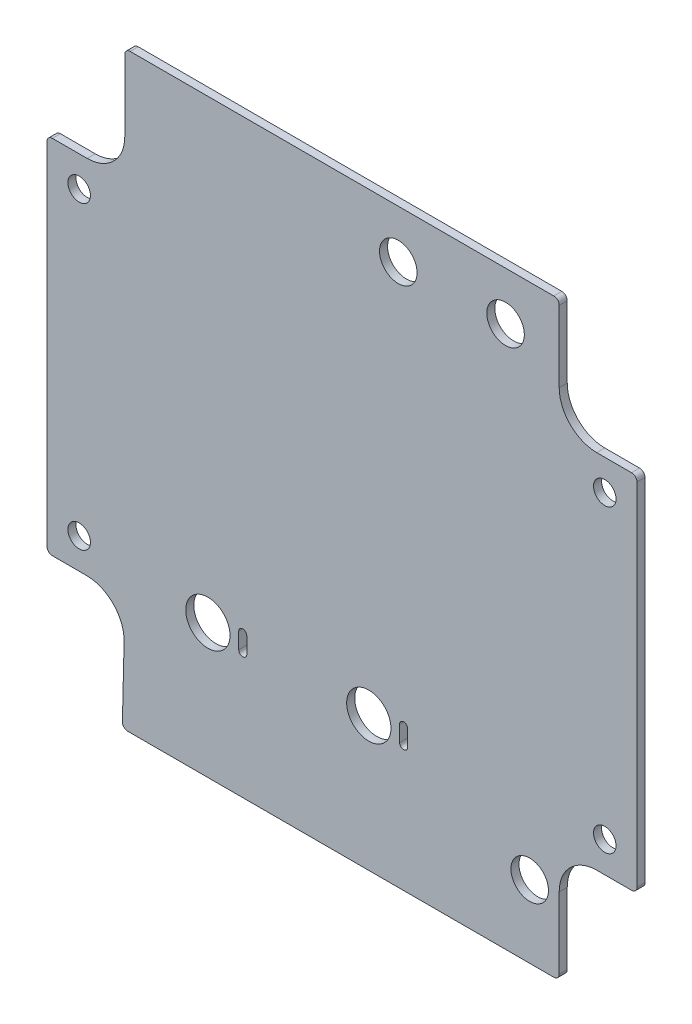
SolidWorks part; units mm, degrees
ref_plane "前基準面" through (0, 0, 0) normal (0, 0, 1) x (1, 0, 0)
ref_plane "上基準面" through (0, 0, 0) normal (0, 1, 0) x (1, 0, 0)
ref_plane "右基準面" through (0, 0, 0) normal (1, 0, 0) x (0, 0, -1)
sketch "草圖1" plane through (0, 0, 0) normal (0, 0, 1) x (1, 0, 0)
  line L27 (9.5192, -18.9462) -> (9.5192, -5.6591)
  line L28 (8.5192, -4.6591) -> (-70.4808, -4.6591)
  line L29 (-71.4808, -5.6591) -> (-71.4808, -18.9462)
  line L30 (-78.4808, -25.9462) -> (-84.9808, -25.9462)
  line L31 (-85.9808, -26.9462) -> (-85.9808, -92.3419)
  line L32 (-84.9834, -93.3419) -> (-78.5836, -93.3586)
  line L33 (-71.6039, -100.5265) -> (-71.9185, -113.6351)
  line L34 (-70.9188, -114.6591) -> (8.5192, -114.6591)
  line L35 (9.5192, -113.6591) -> (9.5192, -100.372)
  line L36 (16.5192, -93.372) -> (23.0192, -93.372)
  line L37 (24.0192, -92.372) -> (24.0192, -26.9462)
  line L38 (23.0192, -25.9462) -> (16.5192, -25.9462)
  line L39 (9.5192, -18.9462) -> (9.5192, -5.6591)
  line L40 (8.5192, -4.6591) -> (-70.4808, -4.6591)
  line L41 (-71.4808, -5.6591) -> (-71.4808, -18.9462)
  line L42 (-78.4808, -25.9462) -> (-84.9808, -25.9462)
  line L43 (-85.9808, -26.9462) -> (-85.9808, -92.3419)
  line L44 (-84.9834, -93.3419) -> (-78.5836, -93.3586)
  line L45 (-71.6039, -100.5265) -> (-71.9185, -113.6351)
  line L46 (-70.9188, -114.6591) -> (8.5192, -114.6591)
  line L47 (9.5192, -113.6591) -> (9.5192, -100.372)
  line L48 (16.5192, -93.372) -> (23.0192, -93.372)
  line L49 (24.0192, -92.372) -> (24.0192, -26.9462)
  line L50 (23.0192, -25.9462) -> (16.5192, -25.9462)
  arc A24 (9.5192, -18.9462) -> (16.5192, -25.9462) centre (16.5192, -18.9462) ccw
  arc A25 (9.5192, -5.6591) -> (8.5192, -4.6591) centre (8.5192, -5.6591) ccw
  arc A26 (-70.4808, -4.6591) -> (-71.4808, -5.6591) centre (-70.4808, -5.6591) ccw
  arc A27 (-78.4808, -25.9462) -> (-71.4808, -18.9462) centre (-78.4808, -18.9462) ccw
  arc A28 (-84.9808, -25.9462) -> (-85.9808, -26.9462) centre (-84.9808, -26.9462) ccw
  arc A29 (-85.9808, -92.3419) -> (-84.9834, -93.3419) centre (-84.9808, -92.3419) ccw
  arc A30 (-71.6039, -100.5265) -> (-78.5836, -93.3586) centre (-78.6019, -100.3586) ccw
  arc A31 (-71.9185, -113.6351) -> (-70.9188, -114.6591) centre (-70.9188, -113.6591) ccw
  arc A32 (8.5192, -114.6591) -> (9.5192, -113.6591) centre (8.5192, -113.6591) ccw
  arc A33 (16.5192, -93.372) -> (9.5192, -100.372) centre (16.5192, -100.372) ccw
  arc A34 (23.0192, -93.372) -> (24.0192, -92.372) centre (23.0192, -92.372) ccw
  arc A35 (24.0192, -26.9462) -> (23.0192, -25.9462) centre (23.0192, -26.9462) ccw
  arc A36 (9.5192, -18.9462) -> (16.5192, -25.9462) centre (16.5192, -18.9462) ccw
  arc A37 (9.5192, -5.6591) -> (8.5192, -4.6591) centre (8.5192, -5.6591) ccw
  arc A38 (-70.4808, -4.6591) -> (-71.4808, -5.6591) centre (-70.4808, -5.6591) ccw
  arc A39 (-78.4808, -25.9462) -> (-71.4808, -18.9462) centre (-78.4808, -18.9462) ccw
  arc A40 (-84.9808, -25.9462) -> (-85.9808, -26.9462) centre (-84.9808, -26.9462) ccw
  arc A41 (-85.9808, -92.3419) -> (-84.9834, -93.3419) centre (-84.9808, -92.3419) ccw
  arc A42 (-71.6039, -100.5265) -> (-78.5836, -93.3586) centre (-78.6019, -100.3586) ccw
  arc A43 (-71.9185, -113.6351) -> (-70.9188, -114.6591) centre (-70.9188, -113.6591) ccw
  arc A44 (8.5192, -114.6591) -> (9.5192, -113.6591) centre (8.5192, -113.6591) ccw
  arc A45 (16.5192, -93.372) -> (9.5192, -100.372) centre (16.5192, -100.372) ccw
  arc A46 (23.0192, -93.372) -> (24.0192, -92.372) centre (23.0192, -92.372) ccw
  arc A47 (24.0192, -26.9462) -> (23.0192, -25.9462) centre (23.0192, -26.9462) ccw
  dimension "D2" = 2
extrude "填料-伸長1" add sketch "草圖1" along normal blind 1.5
hole_wizard "M4 螺旋的螺孔鑽1" positions "草圖4" profile "草圖3" hole size "M4x0.7" standard "Ansi Metric" end condition through all
sketch "草圖4" plane through (0, 0, 0) normal (0, 0, -1) x (-1, 0, 0)
  point P0 (79.9808, -87.644)
  point P3 (-18.0192, -87.644)
  point P6 (-18.0192, -31.644)
  point P9 (79.9808, -31.644)
sketch "草圖3" plane through (-79.9808, -87.644, 0) normal (1, 0, 0) x (0, 1, 0)
  line L0 (0, 0) -> (0, 1.5)
  line L1 (0, 1.5) -> (2.1, 1.5)
  line L2 (2.1, 1.5) -> (2.1, 0)
  line L5 (2.1, 0) -> (0, 0)
  line L11 (0, -6.35) -> (0, 107.95) construction
  dimension "貫穿孔直徑" = 4.2
  dimension "貫穿孔深度" = 1.5
hole_wizard "M8 螺旋的螺孔鑽1" positions "草圖5" profile "草圖6" hole size "M8x1.0" standard "Ansi Metric" end condition through all
sketch "草圖5" plane through (0, 0, 1.5) normal (0, 0, 1) x (1, 0, 0)
  line L0 (-70.9188, -114.6591) -> (8.5192, -114.6591) construction
  line L1 (-85.9808, -26.9462) -> (-85.9808, -92.3419) construction
  point P0 (-55.9808, -89.6591)
  point P3 (-25.9808, -89.6591)
  dimension "D1" = 25
  dimension "D2" = 30
sketch "草圖6" plane through (-55.9808, -89.6591, 1.5) normal (1, 0, 0) x (0, -1, 0)
  line L0 (0, 0) -> (0, 1.5)
  line L1 (0, 1.5) -> (4.125, 1.5)
  line L2 (4.125, 1.5) -> (4.125, 0)
  line L5 (4.125, 0) -> (0, 0)
  line L11 (0, -6.35) -> (0, 107.95) construction
  dimension "貫穿孔直徑" = 8.25
  dimension "貫穿孔深度" = 1.5
sketch "草圖8" plane through (0, 0, 1.5) normal (0, 0, 1) x (1, 0, 0)
  line L0 (9.5192, -113.6591) -> (9.5192, -100.372) construction
  line L1 (-70.9188, -114.6591) -> (8.5192, -114.6591) construction
  circle A0 centre (4.0192, -101.1591) radius 3.5
  dimension "D1" = 7
  dimension "D2" = 5.5
  dimension "D3" = 13.5
extrude "除料-伸長1" cut sketch "草圖8" against normal through all
sketch "草圖9" plane through (0, 0, 1.5) normal (0, 0, 1) x (1, 0, 0)
  line L1 (8.5192, -4.6591) -> (-70.4808, -4.6591) construction
  line L2 (9.5192, -18.9462) -> (9.5192, -5.6591) construction
  circle A0 centre (-0.4808, -13.6591) radius 3.5
  circle A1 centre (-20.4808, -13.6591) radius 3.5
  dimension "D1" = 7
  dimension "D2" = 7
  dimension "D3" = 9
  dimension "D4" = 9
  dimension "D6" = 20
  dimension "D5" = 10
extrude "除料-伸長2" cut sketch "草圖9" against normal through all
sketch "草圖10" plane through (0, 0, 1.5) normal (0, 0, 1) x (1, 0, 0)
  line L0 (-49.4808, -91.1591) -> (-49.4808, -88.1591) construction
  line L1 (-50.2308, -91.1591) -> (-50.2308, -88.1591)
  line L2 (-48.7308, -91.1591) -> (-48.7308, -88.1591)
  line L3 (-19.4808, -91.1591) -> (-19.4808, -88.1591) construction
  line L6 (-20.2308, -91.1591) -> (-20.2308, -88.1591)
  line L7 (-18.7308, -91.1591) -> (-18.7308, -88.1591)
  arc A0 (-50.2308, -91.1591) -> (-48.7308, -91.1591) centre (-49.4808, -91.1591) ccw
  arc A1 (-48.7308, -88.1591) -> (-50.2308, -88.1591) centre (-49.4808, -88.1591) ccw
  arc A2 (-20.2308, -91.1591) -> (-18.7308, -91.1591) centre (-19.4808, -91.1591) ccw
  arc A5 (-18.7308, -88.1591) -> (-20.2308, -88.1591) centre (-19.4808, -88.1591) ccw
  circle A6 centre (-55.9808, -89.6591) radius 4.125 construction
  circle A7 centre (-25.9808, -89.6591) radius 4.125 construction
  point P2 (-49.4808, -89.6591)
  point P9 (0, 0)
  point P10 (0, 0)
  point P11 (-19.4808, -89.6591)
  point P20 (0, 0)
  point P21 (0, 0)
  point P22 (-18.7308, -91)
  point P25 (-21.0328, -89.4774)
  dimension "D1" = 6.5
  dimension "D2" = 6.5
  dimension "D3" = 0
extrude "除料-伸長3" cut sketch "草圖10" along direction (0, 0, -1) on the side against the normal through all
